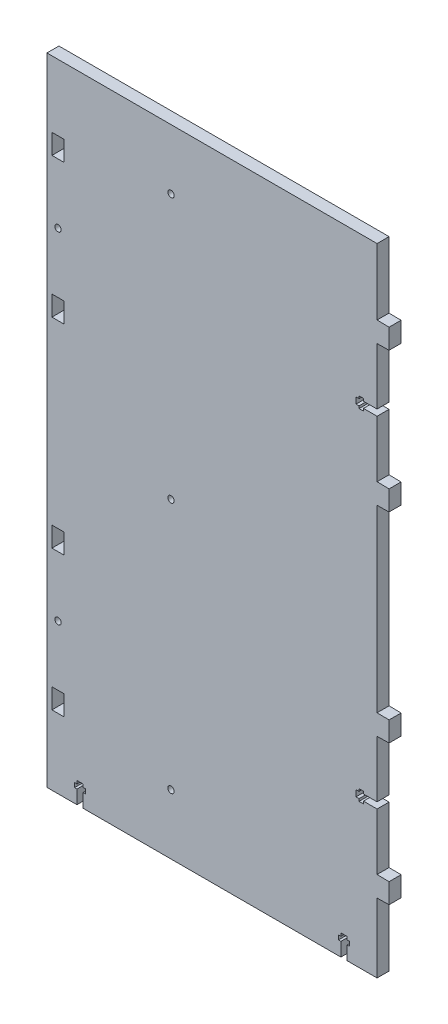
SolidWorks part; units mm, degrees
material "Клен"
ref_plane "Front" through (0, 0, 0) normal (0, 0, 1) x (1, 0, 0)
ref_plane "Top" through (0, 0, 0) normal (0, 1, 0) x (1, 0, 0)
ref_plane "Right" through (0, 0, 0) normal (1, 0, 0) x (0, 0, -1)
sketch "Эскиз1" plane through (0, 0, 0) normal (0, 0, 1) x (1, 0, 0)
  line L1 (975.7199, 850.9685) -> (975.7199, 499.7864) construction
  line L16 (922.3199, 553.2385) -> (922.3199, 563.2385)
  line L17 (916.2199, 553.2385) -> (922.3199, 553.2385)
  line L18 (916.2199, 563.2385) -> (916.2199, 553.2385)
  line L19 (922.3199, 563.2385) -> (916.2199, 563.2385)
  line L20 (916.2199, 623.2385) -> (922.3199, 623.2385)
  line L21 (922.3199, 623.2385) -> (922.3199, 633.2385)
  line L22 (922.3199, 633.2385) -> (916.2199, 633.2385)
  line L23 (916.2199, 633.2385) -> (916.2199, 623.2385)
  line L24 (916.2199, 723.2385) -> (922.3199, 723.2385)
  line L25 (922.3199, 723.2385) -> (922.3199, 733.2385)
  line L26 (916.2199, 733.2385) -> (916.2199, 723.2385)
  line L27 (922.3199, 733.2385) -> (916.2199, 733.2385)
  line L28 (922.3199, 793.2385) -> (922.3199, 803.2385)
  line L29 (922.3199, 803.2385) -> (916.2199, 803.2385)
  line L30 (916.2199, 803.2385) -> (916.2199, 793.2385)
  line L31 (916.2199, 793.2385) -> (922.3199, 793.2385)
  line L32 (978.7199, 858.5777) -> (978.7199, 499.7864) construction
  line L33 (1078.7199, 858.5777) -> (1078.7199, 499.7864) construction
  line L34 (1078.7199, 623.0385) -> (1084.7199, 623.1385)
  line L35 (1068.2199, 764.6885) -> (1069.7199, 764.6885)
  line L36 (1084.7199, 553.1385) -> (1084.7199, 563.1385)
  line L37 (1071.9199, 591.5885) -> (1071.9199, 590.3885)
  line L38 (1071.9199, 761.5885) -> (1071.9199, 760.3885)
  line L39 (1071.9199, 765.8885) -> (1071.9199, 764.6885)
  line L40 (1084.7199, 793.1385) -> (1084.7199, 803.1385)
  line L41 (1084.7199, 723.1385) -> (1084.7199, 733.1385)
  line L42 (1068.2199, 761.5885) -> (1068.2199, 764.6885)
  line L43 (1069.7199, 590.3885) -> (1069.7199, 591.5885)
  line L44 (1068.2199, 591.5885) -> (1068.2199, 594.6885)
  line L45 (1084.7199, 733.1385) -> (1078.7199, 733.2385)
  line L46 (1084.7199, 633.1385) -> (1078.7199, 633.2385)
  line L47 (1078.7199, 633.2385) -> (1078.7199, 723.0385)
  line L48 (1084.7199, 803.1385) -> (1078.7199, 803.2385)
  line L49 (1071.9199, 595.8885) -> (1071.9199, 594.6885)
  line L50 (1078.7199, 793.0385) -> (1084.7199, 793.1385)
  line L51 (1078.7199, 733.2385) -> (1078.7199, 761.5885)
  line L52 (1068.2199, 594.6885) -> (1069.7199, 594.6885)
  line L53 (1071.9199, 760.3885) -> (1069.7199, 760.3885)
  line L54 (1069.7199, 761.5885) -> (1068.2199, 761.5885)
  line L55 (1069.7199, 765.8885) -> (1071.9199, 765.8885)
  line L112 (931.8199, 525.2362) -> (931.8199, 518.4362)
  line L113 (931.8199, 518.4362) -> (978.7199, 518.4362)
  line L155 (978.7199, 836.3385) -> (913.7199, 836.3385)
  line L156 (913.7199, 836.3385) -> (913.7199, 518.4362)
  line L157 (913.7199, 518.4362) -> (928.7199, 518.4362)
  line L158 (928.7199, 518.4362) -> (928.7199, 525.2362)
  line L159 (928.7199, 525.2362) -> (927.5199, 525.2362)
  line L160 (927.5199, 525.2362) -> (927.5199, 527.4362)
  line L161 (927.5199, 527.4362) -> (928.7199, 527.4362)
  line L162 (928.7199, 527.4362) -> (928.7199, 528.9362)
  line L163 (928.7199, 528.9362) -> (931.8199, 528.9362)
  line L164 (931.8199, 528.9362) -> (931.8199, 527.4362)
  line L165 (931.8199, 527.4362) -> (933.0199, 527.4362)
  line L166 (933.0199, 527.4362) -> (933.0199, 525.2362)
  line L167 (933.0199, 525.2362) -> (931.8199, 525.2362)
  line L168 (1069.7199, 594.6885) -> (1069.7199, 595.8885)
  line L169 (1078.7199, 594.6885) -> (1078.7199, 623.0385)
  line L170 (1071.9199, 764.6885) -> (1078.7199, 764.6885)
  line L171 (1084.7199, 563.1385) -> (1078.7199, 563.2385)
  line L172 (1084.7199, 623.1385) -> (1084.7199, 633.1385)
  line L173 (1069.7199, 764.6885) -> (1069.7199, 765.8885)
  line L174 (1078.7199, 553.0385) -> (1084.7199, 553.1385)
  line L175 (1078.7199, 563.2385) -> (1078.7199, 591.5885)
  line L176 (1078.7199, 761.5885) -> (1071.9199, 761.5885)
  line L177 (1078.7199, 518.4362) -> (1078.7199, 553.0385)
  line L178 (1069.7199, 591.5885) -> (1068.2199, 591.5885)
  line L179 (1069.7199, 595.8885) -> (1071.9199, 595.8885)
  line L180 (1069.7199, 760.3885) -> (1069.7199, 761.5885)
  line L181 (1078.7199, 591.5885) -> (1071.9199, 591.5885)
  line L182 (1071.9199, 594.6885) -> (1078.7199, 594.6885)
  line L183 (1078.7199, 803.2385) -> (1078.7199, 836.3385)
  line L184 (1071.9199, 590.3885) -> (1069.7199, 590.3885)
  line L185 (1078.7199, 723.0385) -> (1084.7199, 723.1385)
  line L186 (1078.7199, 764.6885) -> (1078.7199, 793.0385)
  line L187 (978.7199, 836.3385) -> (1078.7199, 836.3385)
  line L188 (978.7199, 518.4362) -> (1060.6199, 518.4362)
  line L189 (1059.4199, 527.4362) -> (1060.6199, 527.4362)
  line L190 (1060.6199, 518.4362) -> (1060.6199, 525.2362)
  line L191 (1064.9199, 525.2362) -> (1063.7199, 525.2362)
  line L192 (1060.6199, 527.4362) -> (1060.6199, 528.9362)
  line L193 (1060.6199, 528.9362) -> (1063.7199, 528.9362)
  line L194 (1060.6199, 525.2362) -> (1059.4199, 525.2362)
  line L195 (1063.7199, 525.2362) -> (1063.7199, 518.4362)
  line L196 (1063.7199, 528.9362) -> (1063.7199, 527.4362)
  line L197 (1063.7199, 527.4362) -> (1064.9199, 527.4362)
  line L198 (1059.4199, 525.2362) -> (1059.4199, 527.4362)
  line L199 (1064.9199, 527.4362) -> (1064.9199, 525.2362)
  line L200 (1063.7199, 518.4362) -> (1078.7199, 518.4362)
  circle A2 centre (919.2699, 593.2385) radius 1.6
  circle A3 centre (919.2699, 763.2385) radius 1.6
  circle A5 centre (975.7199, 806.3385) radius 1.6
  circle A6 centre (975.7199, 674.1385) radius 1.6
  circle A7 centre (975.7199, 548.4385) radius 1.6
  point P5 (0, 0)
  dimension "D13" = 3.2
  dimension "D14" = 3.2
  dimension "D15" = 3.2
  dimension "D2" = 100
  dimension "D3" = 65
  dimension "D4" = 15
  dimension "D12" = 103
extrude "Бобышка-Вытянуть1" add sketch "Эскиз1" along normal blind 6
